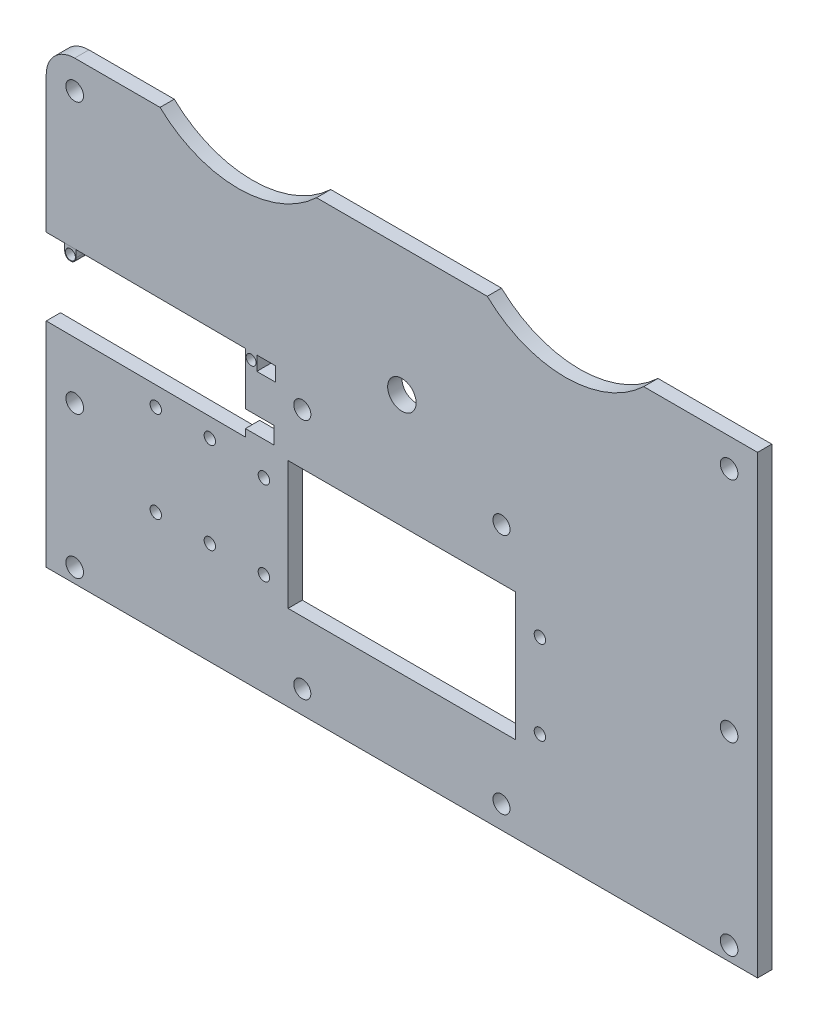
SolidWorks part; units mm, degrees
material "1060-H14"
ref_plane "Plan de face" through (0, 0, 0) normal (0, 0, 1) x (1, 0, 0)
ref_plane "Plan de dessus" through (0, 0, 0) normal (0, 1, 0) x (1, 0, 0)
ref_plane "Plan de droite" through (0, 0, 0) normal (1, 0, 0) x (0, 0, -1)
sketch "Esquisse1" plane through (0, 0, 0) normal (0, 0, 1) x (1, 0, 0)
  line L1 (0, 0) -> (250, 0)
  line L2 (0, 0) -> (0, -160)
  line L3 (0, -160) -> (250, -160)
  line L4 (250, 0) -> (250, -160)
  dimension "D1" = 250
  dimension "D2" = 160
extrude "Boss.-Extru.1" add sketch "Esquisse1" along normal blind 5
sketch "Esquisse3" plane through (0, 0, 5) normal (0, 0, 1) x (1, 0, 0)
  line L0 (0, 0) -> (0, -160) construction
  line L1 (85, -85) -> (125, -85)
  line L2 (85, -85) -> (85, -130)
  line L3 (85, -130) -> (125, -130)
  line L5 (0, -160) -> (250, -160) construction
  line L6 (125, -160) -> (125, 0) construction
  line L7 (125, -85) -> (165, -85)
  line L12 (165, -85) -> (165, -130)
  line L13 (165, -130) -> (125, -130)
  dimension "D1" = 45
  dimension "D2" = 80
  dimension "D3" = 85
  dimension "D4" = 30
extrude "Enlèv. mat.-Extru.2" cut sketch "Esquisse3" against normal blind 35
sketch "Esquisse4" plane through (0, 0, 5) normal (0, 0, 1) x (1, 0, 0)
  line L1 (0, -160) -> (250, -160) construction
  line L2 (0, -160) -> (250, -160) construction
  line L3 (250, 0) -> (0, 0) construction
  line L4 (0, 0) -> (0, -160) construction
  line L5 (250, 0) -> (0, 0) construction
  line L6 (250, -160) -> (250, 0) construction
  circle A0 centre (10, -10) radius 3.1
  circle A1 centre (10, -155) radius 3.1
  circle A2 centre (240, -155) radius 3.1
  circle A3 centre (240, -10) radius 3.1
  dimension "D5" = 6.2
  dimension "D6" = 6.2
  dimension "D11" = 6.2
  dimension "D12" = 6.2
  dimension "D1" = 10
  dimension "D2" = 10
  dimension "D3" = 5
  dimension "D4" = 10
  dimension "D7" = 5
  dimension "D8" = 10
  dimension "D9" = 10
  dimension "D10" = 10
extrude "Enlèv. mat.-Extru.3" cut sketch "Esquisse4" against normal blind 10
sketch "Esquisse5" plane through (0, 0, 0) normal (0, 0, -1) x (-1, 0, 0)
  line L0 (0, 0) -> (0, -160) construction
  line L1 (-250, 0) -> (0, 0) construction
  line L2 (-125, -160) -> (-125, 0) construction
  line L8 (-10, 0) -> (0, 0)
  line L9 (0, 0) -> (0, -10)
  line L10 (0, -160) -> (-250, -160) construction
  line L11 (-250, 0) -> (0, 0) construction
  line L12 (-250, 0) -> (-250, -10)
  line L13 (-240, 0) -> (-250, 0)
  arc A0 (0, -10) -> (-10, 0) centre (-10, -10) ccw
  arc A3 (-250, -10) -> (-240, 0) centre (-240, -10) cw
  dimension "D1" = 10
  dimension "D2" = 10
  dimension "D3" = 10
extrude "Enlèv. mat.-Extru.4" cut sketch "Esquisse5" against normal blind 10
sketch "Esquisse7" plane through (0, 0, 0) normal (0, 0, -1) x (-1, 0, 0)
  line L0 (0, -160) -> (-250, -160) construction
  line L1 (0, -10) -> (0, -160) construction
  line L2 (-250, -160) -> (-250, 0) construction
  circle A0 centre (-90, -152) radius 3
  circle A1 centre (-90, -67) radius 3
  circle A2 centre (-160, -67) radius 3
  circle A3 centre (-160, -152) radius 3
  dimension "D7" = 6
  dimension "D8" = 6
  dimension "D9" = 6
  dimension "D10" = 6
  dimension "D1" = 85
  dimension "D2" = 85
  dimension "D3" = 8
  dimension "D4" = 8
  dimension "D5" = 90
  dimension "D6" = 90
extrude "Enlèv. mat.-Extru.6" cut sketch "Esquisse7" against normal blind 10
sketch "Esquisse8" plane through (0, 0, 0) normal (0, 0, -1) x (-1, 0, 0)
  line L0 (0, -10) -> (0, -160) construction
  line L1 (-250, -160) -> (-250, 0) construction
  circle A0 centre (-10, -105) radius 3.1
  circle A1 centre (-240, -90) radius 3.1
  circle A2 centre (-10, -155) radius 3.1 construction
  circle A3 centre (-240, -155) radius 3.1 construction
  dimension "D1" = 6.2
  dimension "D2" = 6.2
  dimension "D3" = 10
  dimension "D4" = 10
  dimension "D5" = 50
  dimension "D6" = 65
extrude "Enlèv. mat.-Extru.7" cut sketch "Esquisse8" against normal blind 10
sketch "Esquisse11" plane through (0, 0, 0) normal (0, 0, -1) x (-1, 0, 0)
  line L0 (0, -85) -> (-69.9991, -85.3624)
  line L2 (-69.9991, -85.3624) -> (-69.9991, -58.3624)
  line L3 (-69.9991, -58.3624) -> (0, -58)
  line L7 (-250, 0) -> (-10, 0) construction
  line L8 (0, -85) -> (0, -58)
  line L9 (0, -10) -> (0, -160) construction
  dimension "D1" = 58
  dimension "D2" = 70
  dimension "D3" = 27
extrude "Enlèv. mat.-Extru.10" cut sketch "Esquisse11" against normal blind 10
sketch "Esquisse12" plane through (0, 0, 0) normal (0, 0, -1) x (-1, 0, 0)
  line L0 (-6.5, -60.5337) -> (-6.5, -58.0337)
  line L1 (0, -58) -> (-69.9991, -58.3624) construction
  line L2 (-10.5, -60.5544) -> (-10.5, -58.0544)
  line L4 (0, -10) -> (0, -58) construction
  arc A0 (-6.5, -60.5337) -> (-10.5, -60.5544) centre (-8.5001, -60.5337) cw
  circle A1 centre (-8.5001, -60.5337) radius 1.75
  line M33 (-69.9991, -58.3624) -> (0, -58)
  dimension "D1" = 6.5
  dimension "D4" = 3.5
  dimension "D2" = 2.5
  dimension "D3" = 2.5
  dimension "D5" = 4
extrude "Boss.-Extru.2" add sketch "Esquisse12" against normal blind 5 separate body contours A1 L2 A0 L0 M33
sketch "Esquisse13" plane through (0, 0, 5) normal (0, 0, 1) x (1, 0, 0)
  line L0 (69.9991, -63.3624) -> (80.4991, -63.3624)
  line L1 (69.9991, -85.3624) -> (69.9991, -58.3624) construction
  line L3 (80.4991, -63.3624) -> (80.4991, -58.3624)
  line L4 (80.4991, -58.3624) -> (69.9991, -58.3624)
  line L5 (69.9991, -63.3624) -> (69.9991, -58.3624)
  dimension "D1" = 5
  dimension "D2" = 10.5
extrude "Enlèv. mat.-Extru.12" cut sketch "Esquisse13" against normal blind 5
sketch "Esquisse14" plane through (0, 0, 5) normal (0, 0, 1) x (1, 0, 0)
  line L1 (69.9991, -63.3624) -> (80.4991, -63.3624) construction
  line L2 (74, -63.3624) -> (70, -63.3624)
  line L3 (74, -63.3624) -> (74, -58.3624)
  line L4 (74, -58.3624) -> (70, -58.3624)
  line L5 (70, -63.3624) -> (70, -58.3624)
  line L6 (74, -63.3624) -> (70, -58.3624) construction
  line L7 (74, -58.3624) -> (70, -63.3624) construction
  line L9 (70, -62.8069) -> (70, -57.8069) construction
  circle A1 centre (72, -60.8624) radius 1.75
  point P8 (72, -60.8624)
  dimension "D1" = 3.5
  dimension "D2" = 4
  dimension "D4" = 5
sketch "Esquisse16" plane through (0, 0, 5) normal (0, 0, 1) x (1, 0, 0)
  line L0 (69.9991, -76.7624) -> (79.9991, -76.7624)
  line L3 (79.9991, -76.7624) -> (79.9991, -82.7624)
  line L4 (79.9991, -82.7624) -> (69.9991, -82.7624)
  line L5 (69.9991, -82.7624) -> (69.9991, -76.7624)
  line L9 (69.9991, -85.3624) -> (69.9991, -63.3624) construction
  dimension "D1" = 6
  dimension "D2" = 2.6
  dimension "D3" = 10
extrude "Enlèv. mat.-Extru.14" cut sketch "Esquisse16" against normal blind 5 contours L5 L0 L3 L4
sketch "Esquisse17" plane through (0, 0, 5) normal (0, 0, 1) x (1, 0, 0)
  line L0 (250, 0) -> (10, 0) construction
  line L1 (250, -160) -> (250, 0) construction
  line L2 (125, -160) -> (125, 0) construction
  line L4 (0, -160) -> (250, -160) construction
  line L5 (210, 0) -> (155, 0)
  line L6 (95, 0) -> (40, 0)
  arc A0 (210, 0) -> (155, 0) centre (182.5, 29.0474) cw
  arc A1 (40, 0) -> (95, 0) centre (67.5, 29.0474) ccw
  dimension "D3" = 40
  dimension "D1" = 40
  dimension "D2" = 55
extrude "Enlèv. mat.-Extru.15" cut sketch "Esquisse17" against normal blind 10
sketch "Esquisse18" plane through (0, 0, 5) normal (0, 0, 1) x (1, 0, 0)
  line L0 (250, -160) -> (250, 0) construction
  line L1 (155, 0) -> (95, 0) construction
  circle A0 centre (125, -45) radius 5
  dimension "D1" = 10
  dimension "D2" = 125
  dimension "D3" = 45
extrude "Enlèv. mat.-Extru.16" cut sketch "Esquisse18" against normal blind 10
sketch "Esquisse19" plane through (0, 0, 5) normal (0, 0, 1) x (1, 0, 0)
  line L0 (165, -130) -> (165, -85) construction
  line L1 (0, -160) -> (250, -160) construction
  line L2 (125, -160) -> (125, 0) construction
  line L3 (155, 0) -> (95, 0) construction
  circle A0 centre (173.5, -124) radius 2
  circle A1 centre (173.5, -94.5) radius 2
  circle A6 centre (76.5, -94.5) radius 2
  circle A7 centre (76.5, -124) radius 2
  dimension "D3" = 4
  dimension "D4" = 4
  dimension "D7" = 29.5
  dimension "D9" = 8.5
  dimension "D10" = 8.5
  dimension "D11" = 36
extrude "Enlèv. mat.-Extru.17" cut sketch "Esquisse19" against normal blind 29.95
sketch "Esquisse21" plane through (0, 0, 5) normal (0, 0, 1) x (1, 0, 0)
  circle A0 centre (38.5, -124) radius 2
  circle A1 centre (57.5, -124) radius 2.0018
  circle A2 centre (38.5, -92) radius 2
  circle A3 centre (57.5, -92) radius 2
extrude "Enlèv. mat.-Extru.18" cut sketch "Esquisse21" against normal blind 10
extrude "Boss.-Extru.3" add sketch "Esquisse14" against normal up to surface (5 mm away) up to face at (59.5018, -124, 0)
